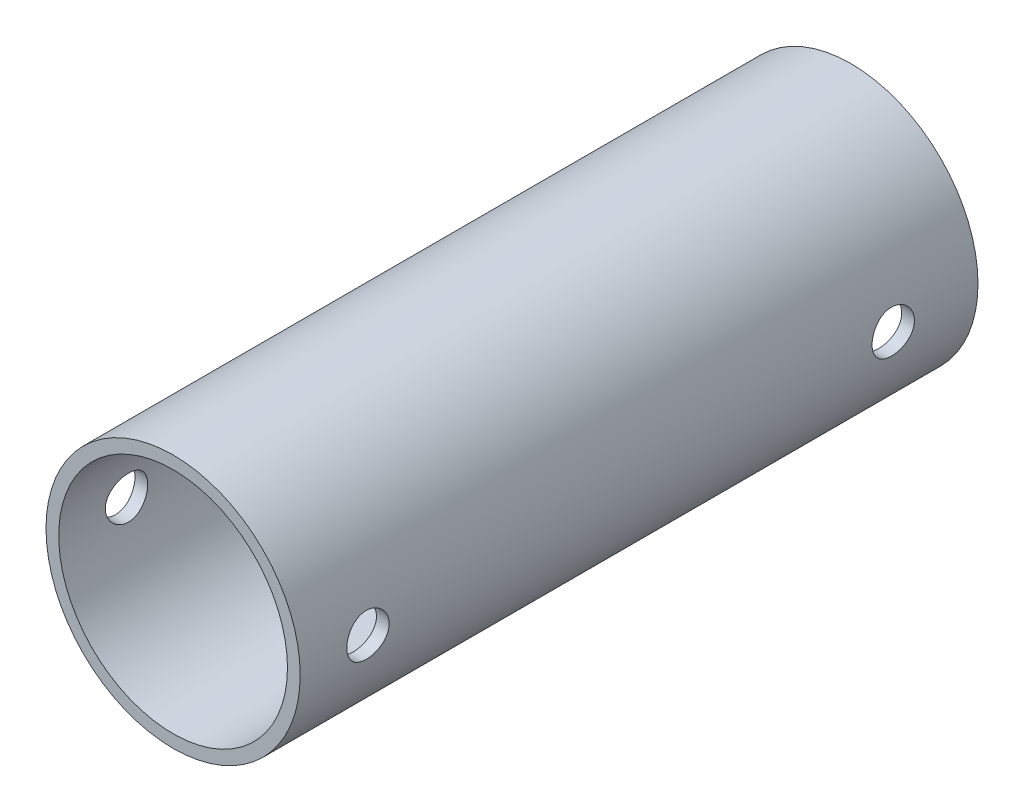
SolidWorks part; units mm, degrees
ref_plane "Front Plane" through (0, 0, 0) normal (0, 0, 1) x (1, 0, 0)
ref_plane "Top Plane" through (0, 0, 0) normal (0, 1, 0) x (1, 0, 0)
ref_plane "Right Plane" through (0, 0, 0) normal (1, 0, 0) x (0, 0, -1)
sketch "Sketch1" plane through (0, 0, 0) normal (0, 0, 1) x (1, 0, 0)
  circle A0 centre (0, 0) radius 15
  circle A1 centre (0, 0) radius 13.5
  dimension "D1" = 30
  dimension "D2" = 1.5
extrude "Boss-Extrude1" add sketch "Sketch1" along normal blind 80
sketch "Sketch2" plane through (0, 0, 0) normal (1, 0, 0) x (0, 0, -1)
  line L0 (-80, 15) -> (-80, -15) construction
  circle A0 centre (-10, 0) radius 2.5
  circle A1 centre (-72, 0) radius 2.5
  dimension "D1" = 5
  dimension "D3" = 5
  dimension "D2" = 10
  dimension "D4" = 8
extrude "Cut-Extrude1" cut sketch "Sketch2" against normal mid plane 54
